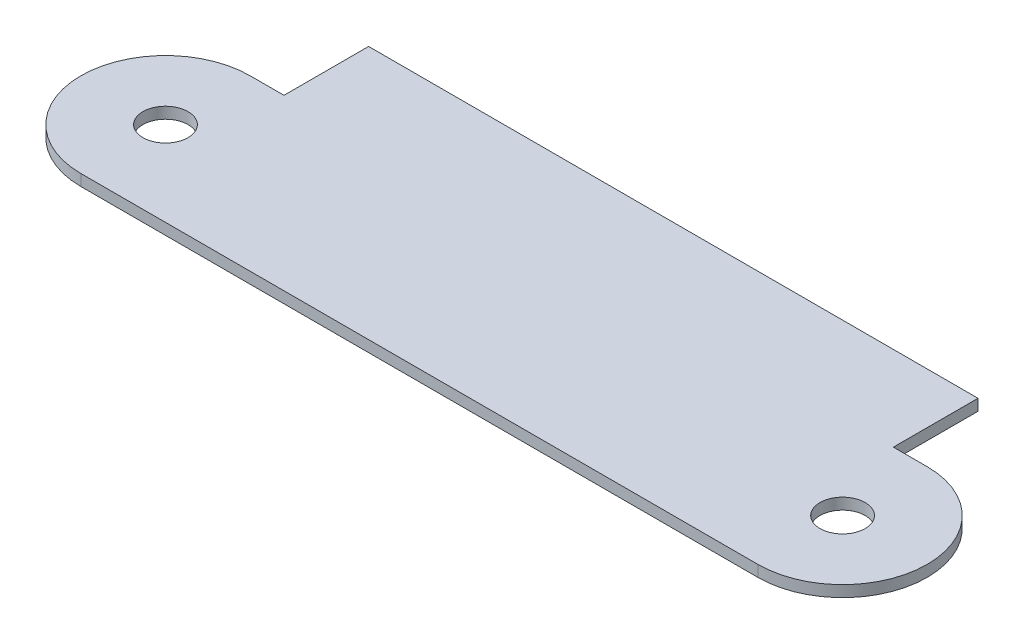
SolidWorks part; units mm, degrees
ref_plane "Front Plane" through (0, 0, 0) normal (0, 0, 1) x (1, 0, 0)
ref_plane "Top Plane" through (0, 0, 0) normal (0, 1, 0) x (1, 0, 0)
ref_plane "Right Plane" through (0, 0, 0) normal (1, 0, 0) x (0, 0, -1)
sketch "Sketch1" plane through (0, 0, 0) normal (0, 1, 0) x (1, 0, 0)
  line L0 (0, 0) -> (60, 0) construction
  line L1 (0, 7.5) -> (0, -7.5) construction
  line L4 (0, -7.5) -> (60, -7.5)
  line L5 (60, -7.5) -> (60, 7.5) construction
  line L6 (60, 7.5) -> (0, 7.5) construction
  line L7 (0, 7.5) -> (3, 7.5)
  line L8 (3, 7.5) -> (3, 15)
  line L9 (3, 15) -> (57, 15)
  line L10 (57, 15) -> (57, 7.5)
  line L11 (57, 7.5) -> (60, 7.5)
  line L12 (30, 0) -> (30, 15) construction
  circle A0 centre (0, 0) radius 2
  circle A1 centre (60, 0) radius 2
  arc A4 (0, 7.5) -> (0, -7.5) centre (0, 0) ccw
  arc A5 (60, 7.5) -> (60, -7.5) centre (60, 0) cw
  dimension "D1" = 60
  dimension "D2" = 4
  dimension "D4" = 3
  dimension "D3" = 15
  dimension "D5" = 7.5
extrude "Boss-Extrude1" add sketch "Sketch1" along normal blind 1 contours A5 L11 L10 L9 L8 L7 A4 L4 A1 A0
